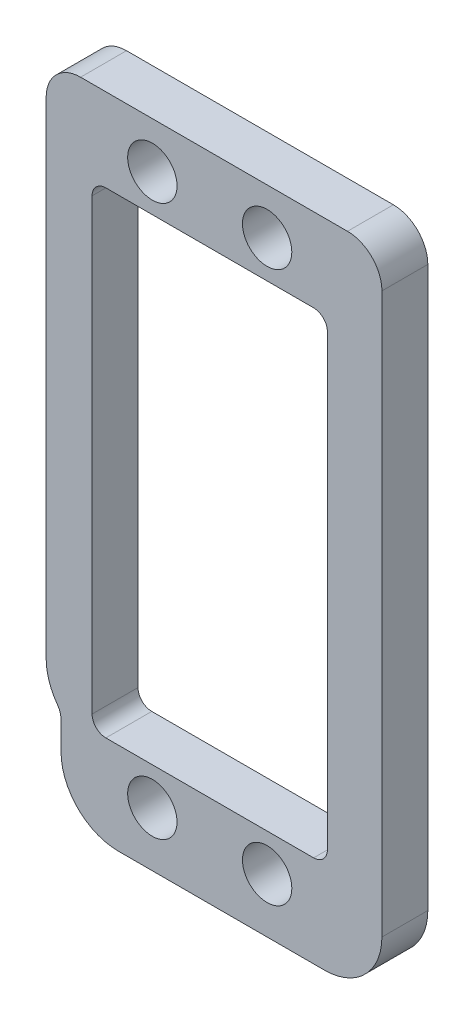
SolidWorks part; units mm, degrees
material "玻纤"
ref_plane "前视基准面" through (0, 0, 0) normal (0, 0, 1) x (1, 0, 0)
ref_plane "上视基准面" through (0, 0, 0) normal (0, 1, 0) x (1, 0, 0)
ref_plane "右视基准面" through (0, 0, 0) normal (1, 0, 0) x (0, 0, -1)
sketch "草图1" plane through (0, 0, 0) normal (0, 0, 1) x (1, 0, 0)
  line L1 (0, 0) -> (100, 0)
  line L2 (0, 0) -> (0, -100)
  line L3 (0, -100) -> (100, -100)
  line L4 (100, 0) -> (100, -100)
  dimension "D1" = 100
  dimension "D2" = 100
extrude "凸台-拉伸1" add sketch "草图1" along normal blind 4
sketch "草图2" plane through (0, 0, 4) normal (0, 0, 1) x (1, 0, 0)
  line L4 (0, 0) -> (0, -100)
  line L5 (0, -100) -> (100, -100)
  line L6 (100, -100) -> (100, 0)
  line L7 (100, 0) -> (0, 0)
  line L8 (0, 0) -> (0, -100)
  line L9 (0, -100) -> (100, -100)
  line L10 (100, -100) -> (100, 0)
  line L11 (100, 0) -> (0, 0)
  circle A0 centre (80, -66) radius 2.15
  circle A1 centre (90, -66) radius 2.15
  circle A2 centre (90, -18) radius 2.15
  circle A3 centre (80, -18) radius 2.15
  dimension "D2" = 4.3
  dimension "D5" = 10
  dimension "D6" = 48
  dimension "D7" = 18
  dimension "D8" = 10
  dimension "D1" = 0
  dimension "D3" = 2
  dimension "D4" = 2
extrude "切除-拉伸1" cut sketch "草图2" against normal through all contours A3 | A2 | A0 | A1
sketch "草图3" plane through (0, 0, 4) normal (0, 0, 1) x (1, 0, 0)
  line L4 (0, 0) -> (0, -100)
  line L5 (0, -100) -> (100, -100)
  line L6 (100, -100) -> (100, 0)
  line L7 (100, 0) -> (0, 0)
  line L8 (0, 0) -> (0, -100)
  line L9 (0, -100) -> (100, -100)
  line L10 (100, -100) -> (100, 0)
  line L11 (100, 0) -> (0, 0)
  circle A0 centre (73, -95) radius 1.65
  circle A1 centre (73, -85) radius 1.65
  circle A2 centre (85, -85) radius 1.65
  circle A3 centre (85, -95) radius 1.65
  dimension "D2" = 3.3
  dimension "D5" = 10
  dimension "D6" = 12
  dimension "D7" = 5
  dimension "D8" = 15
  dimension "D1" = 0
  dimension "D3" = 2
  dimension "D4" = 2
extrude "切除-拉伸2" cut sketch "草图3" against normal through all contours A1 | A2 | A3 | A0
sketch "草图4" plane through (0, 0, 4) normal (0, 0, 1) x (1, 0, 0)
  line L4 (0, 0) -> (0, -100)
  line L5 (0, -100) -> (100, -100)
  line L6 (100, -100) -> (100, 0)
  line L7 (100, 0) -> (0, 0)
  line L8 (0, 0) -> (0, -100)
  line L9 (0, -100) -> (100, -100)
  line L10 (100, -100) -> (100, 0)
  line L11 (100, 0) -> (0, 0)
  circle A0 centre (71.5, -100) radius 9.5
  circle M5 centre (73, -95) radius 1.65
  dimension "D2" = 19
  dimension "D3" = 28.5
  dimension "D1" = 0
extrude "切除-拉伸3" cut sketch "草图4" against normal through all contours L9 A0 M5
sketch "草图5" plane through (0, 0, 4) normal (0, 0, 1) x (1, 0, 0)
  line L0 (85, -1.0404) -> (85, -63.0979) construction
  line L1 (65.9696, -42) -> (93.5663, -42) construction
  line L3 (74.75, -21.25) -> (95.25, -21.25)
  line L4 (74.75, -21.25) -> (74.75, -62.75)
  line L5 (81, -100) -> (100, -100)
  line L6 (100, -100) -> (100, 0)
  line L7 (100, 0) -> (0, 0)
  line L8 (0, 0) -> (0, -100)
  line L9 (0, -100) -> (62, -100)
  line L10 (81, -100) -> (100, -100)
  line L11 (100, -100) -> (100, 0)
  line L12 (100, 0) -> (0, 0)
  line L13 (0, 0) -> (0, -100)
  line L14 (0, -100) -> (62, -100)
  line L15 (74.75, -62.75) -> (95.25, -62.75)
  line L16 (95.25, -21.25) -> (95.25, -62.75)
  circle A0 centre (80, -18) radius 2.15 construction
  arc A1 (81, -100) -> (62, -100) centre (71.5, -100) ccw
  arc A2 (81, -100) -> (62, -100) centre (71.5, -100) ccw
  circle A3 centre (80, -18) radius 2.15
  circle A4 centre (90, -18) radius 2.15 construction
  circle A5 centre (90, -18) radius 2.15
  circle A6 centre (80, -66) radius 2.15 construction
  circle A7 centre (80, -66) radius 2.15
  circle A8 centre (90, -66) radius 2.15 construction
  circle A9 centre (90, -66) radius 2.15
  dimension "D2" = 41.5
  dimension "D3" = 20.5
  dimension "D1" = 0
extrude "切除-拉伸4" cut sketch "草图5" against normal blind 10 contours L4 L3 L16 L15
sketch "草图6" plane through (0, 0, 4) normal (0, 0, 1) x (1, 0, 0)
  line L0 (55, 0) -> (55, -100)
  line L5 (81, -100) -> (100, -100)
  line L6 (100, -100) -> (100, 0)
  line L7 (100, 0) -> (0, 0)
  line L8 (0, 0) -> (0, -100)
  line L9 (0, -100) -> (62, -100)
  line L10 (81, -100) -> (100, -100)
  line L11 (100, -100) -> (100, 0)
  line L12 (100, 0) -> (0, 0)
  line L13 (0, 0) -> (0, -100)
  line L14 (0, -100) -> (62, -100)
  circle A0 centre (73, -85) radius 1.65 construction
  arc A1 (81, -100) -> (62, -100) centre (71.5, -100) ccw
  arc A2 (81, -100) -> (62, -100) centre (71.5, -100) ccw
  circle A3 centre (73, -85) radius 1.65
  dimension "D2" = 45
  dimension "D1" = 0
extrude "切除-拉伸5" cut sketch "草图6" against normal blind 10
fillet "圆角2" radius 1.2 4 edges at (74.75, -21.25, 2) (95.25, -62.75, 2) (74.75, -62.75, 2) (95.25, -21.25, 2)
sketch "草图8" plane through (0, 0, 4) normal (0, 0, 1) x (1, 0, 0)
  line L5 (100, 0) -> (55, 0)
  line L6 (55, 0) -> (55, -100)
  line L7 (55, -100) -> (62, -100)
  line L8 (81, -100) -> (100, -100)
  line L9 (100, -100) -> (100, 0)
  line L10 (100, 0) -> (55, 0)
  line L11 (55, 0) -> (55, -100)
  line L12 (55, -100) -> (62, -100)
  line L13 (81, -100) -> (100, -100)
  line L14 (100, -100) -> (100, 0)
  circle A0 centre (59, -85) radius 1.65
  arc A1 (81, -100) -> (62, -100) centre (71.5, -100) ccw
  arc A2 (81, -100) -> (62, -100) centre (71.5, -100) ccw
  circle A3 centre (73, -85) radius 1.65 construction
  circle A4 centre (73, -85) radius 1.65
  dimension "D2" = 3.3
  dimension "D4" = 14
  dimension "D3" = 0
  dimension "D1" = 0
extrude "切除-拉伸6" cut sketch "草图8" against normal through all contours A0
sketch "草图9" plane through (0, 0, 4) normal (0, 0, 1) x (1, 0, 0)
  line L0 (55, -90.5) -> (71.5, -90.5)
  line L1 (55, -78.5) -> (70.75, -78.5)
  line L2 (70.75, -78.5) -> (70.75, 0)
  line L3 (74.75, -22.45) -> (74.75, -61.55) construction
  line L5 (100, 0) -> (55, 0)
  line L6 (55, 0) -> (55, -100)
  line L7 (55, -100) -> (62, -100)
  line L8 (81, -100) -> (100, -100)
  line L9 (100, -100) -> (100, 0)
  line L10 (100, 0) -> (55, 0)
  line L11 (55, 0) -> (55, -100)
  line L12 (55, -100) -> (62, -100)
  line L13 (81, -100) -> (100, -100)
  line L14 (100, -100) -> (100, 0)
  arc A1 (81, -100) -> (62, -100) centre (71.5, -100) ccw
  arc A2 (81, -100) -> (62, -100) centre (71.5, -100) ccw
  line M26 (100, 0) -> (55, 0)
  line M27 (55, 0) -> (55, -100)
  line M28 (55, -100) -> (62, -100)
  arc M29 (62, -100) -> (81, -100) centre (71.5, -100) cw
  dimension "D2" = 4
  dimension "D3" = 12
  dimension "D1" = 0
extrude "切除-拉伸7" cut sketch "草图9" against normal through all contours L0 M27 M28 M29 | L1 L2 M26 M27
sketch "草图10" plane through (0, 0, 4) normal (0, 0, 1) x (1, 0, 0)
  line L0 (55, -87.5) -> (100, -87.5)
  line L7 (81, -100) -> (100, -100)
  line L8 (100, -100) -> (100, 0)
  line L9 (100, 0) -> (70.75, 0)
  line L10 (70.75, 0) -> (70.75, -78.5)
  line L12 (55, -78.5) -> (55, -90.5)
  line L13 (55, -90.5) -> (71.5, -90.5)
  line L14 (81, -100) -> (100, -100)
  line L15 (100, -100) -> (100, 0)
  line L16 (100, 0) -> (70.75, 0)
  line L17 (70.75, 0) -> (70.75, -78.5)
  line L19 (55, -78.5) -> (55, -90.5)
  line L20 (55, -90.5) -> (71.5, -90.5)
  line L21 (70.75, -78.5) -> (55, -78.5)
  line L22 (70.75, -78.5) -> (55, -78.5)
  arc A8 (81, -100) -> (71.5, -90.5) centre (71.5, -100) ccw
  arc A16 (81, -100) -> (71.5, -90.5) centre (71.5, -100) ccw
  dimension "D2" = 12.5
  dimension "D1" = 0
extrude "切除-拉伸8" cut sketch "草图10" against normal blind 10
fillet "圆角5" radius 3 2 edges at (100, -87.5, 2) (55, -87.5, 2)
sketch "草图11" plane through (0, 0, 4) normal (0, 0, 1) x (1, 0, 0)
  line L0 (70.75, -14) -> (100, -14)
  line L5 (55, -78.5) -> (55, -84.5)
  line L6 (58, -87.5) -> (97, -87.5)
  line L7 (100, -84.5) -> (100, 0)
  line L8 (100, 0) -> (70.75, 0)
  line L9 (70.75, 0) -> (70.75, -78.5)
  line L10 (55, -78.5) -> (55, -84.5)
  line L11 (58, -87.5) -> (97, -87.5)
  line L12 (100, -84.5) -> (100, 0)
  line L13 (100, 0) -> (70.75, 0)
  line L14 (70.75, 0) -> (70.75, -78.5)
  line L17 (70.75, -78.5) -> (55, -78.5)
  line L18 (70.75, -78.5) -> (55, -78.5)
  arc A6 (55, -84.5) -> (58, -87.5) centre (58, -84.5) ccw
  arc A7 (97, -87.5) -> (100, -84.5) centre (97, -84.5) ccw
  arc A10 (55, -84.5) -> (58, -87.5) centre (58, -84.5) ccw
  arc A11 (97, -87.5) -> (100, -84.5) centre (97, -84.5) ccw
  line M31 (100, -84.5) -> (100, 0)
  line M32 (100, 0) -> (70.75, 0)
  line M33 (70.75, 0) -> (70.75, -78.5)
  dimension "D2" = 14
  dimension "D1" = 0
extrude "切除-拉伸9" cut sketch "草图11" against normal blind 10 contours L0 M33 M31 M32
fillet "圆角7" radius 3 2 edges at (70.75, -14, 2) (100, -14, 2)
sketch "草图12" plane through (0, 0, 4) normal (0, 0, 1) x (1, 0, 0)
  line L5 (97, -14) -> (73.75, -14)
  line L6 (70.75, -17) -> (70.75, -78.5)
  line L7 (55, -78.5) -> (55, -84.5)
  line L8 (58, -87.5) -> (97, -87.5)
  line L9 (100, -84.5) -> (100, -17)
  line L10 (97, -14) -> (73.75, -14)
  line L11 (70.75, -17) -> (70.75, -78.5)
  line L12 (55, -78.5) -> (55, -84.5)
  line L13 (58, -87.5) -> (97, -87.5)
  line L14 (100, -84.5) -> (100, -17)
  line L16 (70.75, -78.5) -> (55, -78.5)
  line L17 (70.75, -78.5) -> (55, -78.5)
  circle A0 centre (73, -92.5) radius 10
  circle A1 centre (73, -85) radius 1.65 construction
  circle A2 centre (73, -85) radius 1.65
  arc A6 (73.75, -14) -> (70.75, -17) centre (73.75, -17) ccw
  arc A9 (55, -84.5) -> (58, -87.5) centre (58, -84.5) ccw
  arc A10 (97, -87.5) -> (100, -84.5) centre (97, -84.5) ccw
  arc A11 (100, -17) -> (97, -14) centre (97, -17) ccw
  arc A12 (73.75, -14) -> (70.75, -17) centre (73.75, -17) ccw
  arc A15 (55, -84.5) -> (58, -87.5) centre (58, -84.5) ccw
  arc A16 (97, -87.5) -> (100, -84.5) centre (97, -84.5) ccw
  arc A17 (100, -17) -> (97, -14) centre (97, -17) ccw
  circle M29 centre (73, -85) radius 1.65
  dimension "D3" = 20
  dimension "D2" = 5
  dimension "D1" = 0
extrude "切除-拉伸10" cut sketch "草图12" against normal blind 10 contours L13 A0 M29
fillet "圆角8" radius 3 2 edges at (81.6603, -87.5, 2) (64.3397, -87.5, 2)
sketch "草图13" plane through (0, 0, 4) normal (0, 0, 1) x (1, 0, 0)
  line L0 (55, -78.5) -> (70.75, -51.2202)
  line L7 (83.247, -87.5) -> (97, -87.5)
  line L8 (100, -84.5) -> (100, -17)
  line L9 (97, -14) -> (73.75, -14)
  line L10 (70.75, -17) -> (70.75, -78.5)
  line L11 (70.75, -78.5) -> (55, -78.5)
  line L12 (55, -78.5) -> (55, -84.5)
  line L13 (58, -87.5) -> (62.753, -87.5)
  line L14 (83.247, -87.5) -> (97, -87.5)
  line L15 (100, -84.5) -> (100, -17)
  line L16 (97, -14) -> (73.75, -14)
  line L17 (70.75, -17) -> (70.75, -78.5)
  line L18 (70.75, -78.5) -> (55, -78.5)
  line L19 (55, -78.5) -> (55, -84.5)
  line L20 (58, -87.5) -> (62.753, -87.5)
  arc A7 (80.8823, -86.3462) -> (65.1177, -86.3462) centre (73, -92.5) ccw
  arc A8 (80.8823, -86.3462) -> (83.247, -87.5) centre (83.247, -84.5) ccw
  arc A9 (97, -87.5) -> (100, -84.5) centre (97, -84.5) ccw
  arc A10 (100, -17) -> (97, -14) centre (97, -17) ccw
  arc A11 (73.75, -14) -> (70.75, -17) centre (73.75, -17) ccw
  arc A12 (55, -84.5) -> (58, -87.5) centre (58, -84.5) ccw
  arc A13 (62.753, -87.5) -> (65.1177, -86.3462) centre (62.753, -84.5) ccw
  arc A14 (80.8823, -86.3462) -> (65.1177, -86.3462) centre (73, -92.5) ccw
  arc A15 (80.8823, -86.3462) -> (83.247, -87.5) centre (83.247, -84.5) ccw
  arc A16 (97, -87.5) -> (100, -84.5) centre (97, -84.5) ccw
  arc A17 (100, -17) -> (97, -14) centre (97, -17) ccw
  arc A18 (73.75, -14) -> (70.75, -17) centre (73.75, -17) ccw
  arc A19 (55, -84.5) -> (58, -87.5) centre (58, -84.5) ccw
  arc A20 (62.753, -87.5) -> (65.1177, -86.3462) centre (62.753, -84.5) ccw
  line M24 (70.75, -17) -> (70.75, -78.5)
  line M25 (70.75, -78.5) -> (55, -78.5)
  dimension "D2" = 60
  dimension "D1" = 0
extrude "凸台-拉伸2" add sketch "草图13" against normal blind 4 contours L0 M25 M24
fillet "圆角9" radius 5 2 edges at (70.75, -51.2202, 2) (55, -78.5, 2)
sketch "草图14" plane through (0, 0, 4) normal (0, 0, 1) x (1, 0, 0)
  line L0 (66.616, -50.3805) -> (52.2058, -75.3397)
  line L1 (73.5442, -54.3805) -> (59.134, -79.3397)
  line L2 (59.134, -79.3397) -> (73.5442, -79.3397)
  line L3 (73.5442, -79.3397) -> (73.5442, -54.3805)
  line L4 (75.0442, -79.3397) -> (75.0442, -54.3805)
  line L5 (72.0442, -79.3397) -> (72.0442, -54.3805)
  line L7 (70.0801, -52.3805) -> (55.6699, -77.3397)
  line L8 (55, -79.8397) -> (55, -84.5)
  line L9 (58, -87.5) -> (62.753, -87.5)
  line L10 (83.247, -87.5) -> (97, -87.5)
  line L11 (100, -84.5) -> (100, -17)
  line L12 (97, -14) -> (73.75, -14)
  line L13 (70.75, -17) -> (70.75, -49.8805)
  line L14 (70.0801, -52.3805) -> (55.6699, -77.3397)
  line L15 (55, -79.8397) -> (55, -84.5)
  line L16 (58, -87.5) -> (62.753, -87.5)
  line L17 (83.247, -87.5) -> (97, -87.5)
  line L18 (100, -84.5) -> (100, -17)
  line L19 (97, -14) -> (73.75, -14)
  line L20 (70.75, -17) -> (70.75, -49.8805)
  arc A9 (55.6699, -77.3397) -> (55, -79.8397) centre (60, -79.8397) ccw
  arc A10 (55, -84.5) -> (58, -87.5) centre (58, -84.5) ccw
  arc A11 (62.753, -87.5) -> (65.1177, -86.3462) centre (62.753, -84.5) ccw
  arc A12 (80.8823, -86.3462) -> (65.1177, -86.3462) centre (73, -92.5) ccw
  arc A13 (80.8823, -86.3462) -> (83.247, -87.5) centre (83.247, -84.5) ccw
  arc A14 (97, -87.5) -> (100, -84.5) centre (97, -84.5) ccw
  arc A15 (100, -17) -> (97, -14) centre (97, -17) ccw
  arc A16 (73.75, -14) -> (70.75, -17) centre (73.75, -17) ccw
  arc A17 (70.0801, -52.3805) -> (70.75, -49.8805) centre (65.75, -49.8805) ccw
  arc A18 (55.6699, -77.3397) -> (55, -79.8397) centre (60, -79.8397) ccw
  arc A19 (55, -84.5) -> (58, -87.5) centre (58, -84.5) ccw
  arc A20 (62.753, -87.5) -> (65.1177, -86.3462) centre (62.753, -84.5) ccw
  arc A21 (80.8823, -86.3462) -> (65.1177, -86.3462) centre (73, -92.5) ccw
  arc A22 (80.8823, -86.3462) -> (83.247, -87.5) centre (83.247, -84.5) ccw
  arc A23 (97, -87.5) -> (100, -84.5) centre (97, -84.5) ccw
  arc A24 (100, -17) -> (97, -14) centre (97, -17) ccw
  arc A25 (73.75, -14) -> (70.75, -17) centre (73.75, -17) ccw
  arc A26 (70.0801, -52.3805) -> (70.75, -49.8805) centre (65.75, -49.8805) ccw
  dimension "D4" = 1.5
  dimension "D1" = 0
  dimension "D2" = 4
  dimension "D3" = 4
  dimension "D5" = 1.5
extrude "切除-拉伸11" cut sketch "草图14" against normal blind 10 contours L2 L5 L1
fillet "圆角10" radius 1.7 3 edges at (72.0442, -79.3397, 2) (59.134, -79.3397, 2) (72.0442, -56.9785, 2)
sketch "草图15" plane through (0, 0, 0) normal (0, 0, -1) x (-1, 0, 0)
  line L0 (-100, -84.5) -> (-100, -17) construction
  line L1 (-100, -70.75) -> (-41.6584, -70.75)
  line L2 (-100, -70.75) -> (-100, -90.0787)
  line L3 (-100, -90.0787) -> (-41.6584, -90.0787)
  line L4 (-41.6584, -70.75) -> (-41.6584, -90.0787)
  line L6 (-70.75, -49.8805) -> (-55.6676, -49.8805)
  line L7 (-70.75, -49.8805) -> (-70.75, -70.75)
  line L8 (-70.75, -70.75) -> (-55.6676, -70.75)
  line L9 (-55.6676, -49.8805) -> (-55.6676, -70.75)
  line L11 (-75.95, -62.75) -> (-94.05, -62.75) construction
  line M2 (-72.0442, -77.6397) -> (-72.0442, -63.323)
  arc M3 (-72.0442, -63.323) -> (-68.872, -62.473) centre (-70.3442, -63.323) cw
  line M4 (-68.872, -62.473) -> (-60.6062, -76.7897)
  arc M5 (-60.6062, -76.7897) -> (-62.0785, -79.3397) centre (-62.0785, -77.6397) cw
  line M6 (-62.0785, -79.3397) -> (-70.3442, -79.3397)
  arc M7 (-70.3442, -79.3397) -> (-72.0442, -77.6397) centre (-70.3442, -77.6397) cw
  circle M8 centre (-59, -85) radius 1.65
  circle M13 centre (-85, -85) radius 1.65
  line M22 (-55, -84.5) -> (-55, -79.8397)
  arc M23 (-55, -79.8397) -> (-55.6699, -77.3397) centre (-60, -79.8397) ccw
  line M24 (-55.6699, -77.3397) -> (-70.0801, -52.3805)
  arc M25 (-70.0801, -52.3805) -> (-70.75, -49.8805) centre (-65.75, -49.8805) cw
  line M30 (-100, -17) -> (-100, -84.5)
  arc M31 (-100, -84.5) -> (-97, -87.5) centre (-97, -84.5) ccw
  line M32 (-97, -87.5) -> (-83.247, -87.5)
  arc M33 (-83.247, -87.5) -> (-80.8823, -86.3462) centre (-83.247, -84.5) ccw
  arc M34 (-80.8823, -86.3462) -> (-65.1177, -86.3462) centre (-73, -92.5) cw
  arc M35 (-65.1177, -86.3462) -> (-62.753, -87.5) centre (-62.753, -84.5) ccw
  line M36 (-62.753, -87.5) -> (-58, -87.5)
  arc M37 (-58, -87.5) -> (-55, -84.5) centre (-58, -84.5) ccw
  dimension "D1" = 8
extrude "切除-拉伸12" cut sketch "草图15" against normal blind 10 contours L9 L6 L1 M25 M24 | L4 L1 L2 L3 M24 M23 M22 M37 M36 M35 M34 M33 M32 M31 | L1 M30 M31 M32 M33 M34 M35 M36 M37 M22 M23 M24 M4 M5 M6 M7 M2 M13 M8 | L7 L1 M25 M3 M4 M24
fillet "圆角11" radius 5 3 edges at (100, -70.75, 2) (70.75, -61.6722, 2) (72.0442, -70.75, 2)
